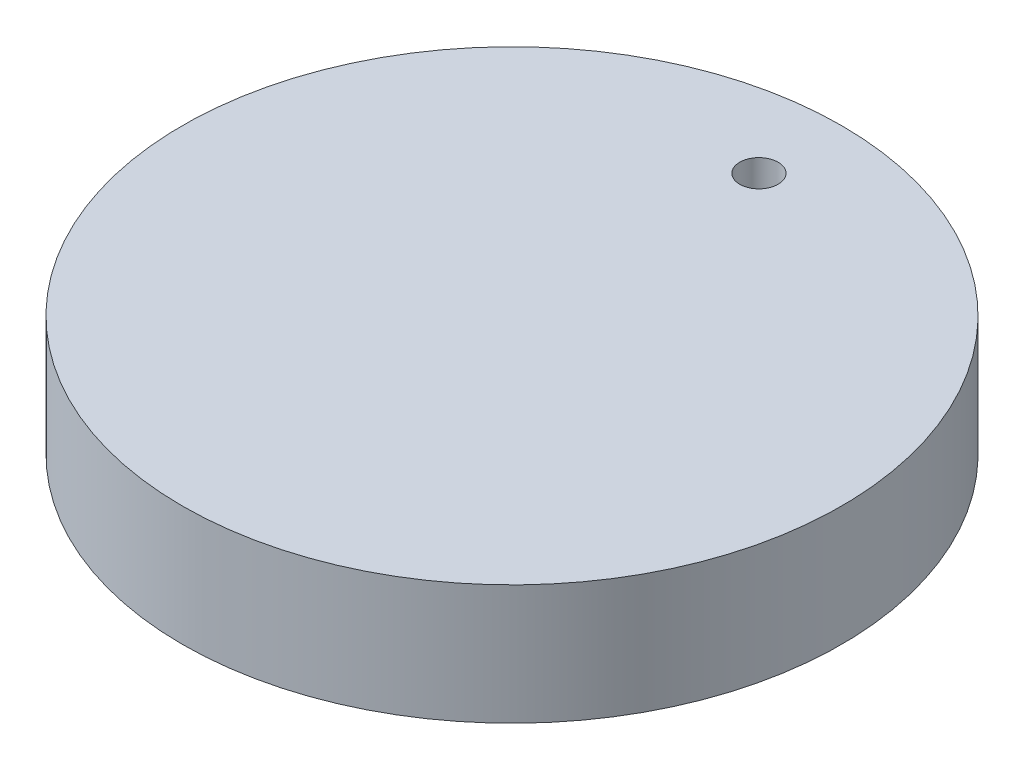
SolidWorks part; units mm, degrees
ref_plane "Front Plane" through (0, 0, 0) normal (0, 0, 1) x (1, 0, 0)
ref_plane "Top Plane" through (0, 0, 0) normal (0, 1, 0) x (1, 0, 0)
ref_plane "Right Plane" through (0, 0, 0) normal (1, 0, 0) x (0, 0, -1)
sketch "Sketch1" plane through (0, 0, 0) normal (0, 1, 0) x (1, 0, 0)
  circle A0 centre (0, 0) radius 55
  circle A1 centre (0, 41.2108) radius 3.2
  dimension "D1" = 110
extrude "Boss-Extrude1" add sketch "Sketch1" along normal blind 20
